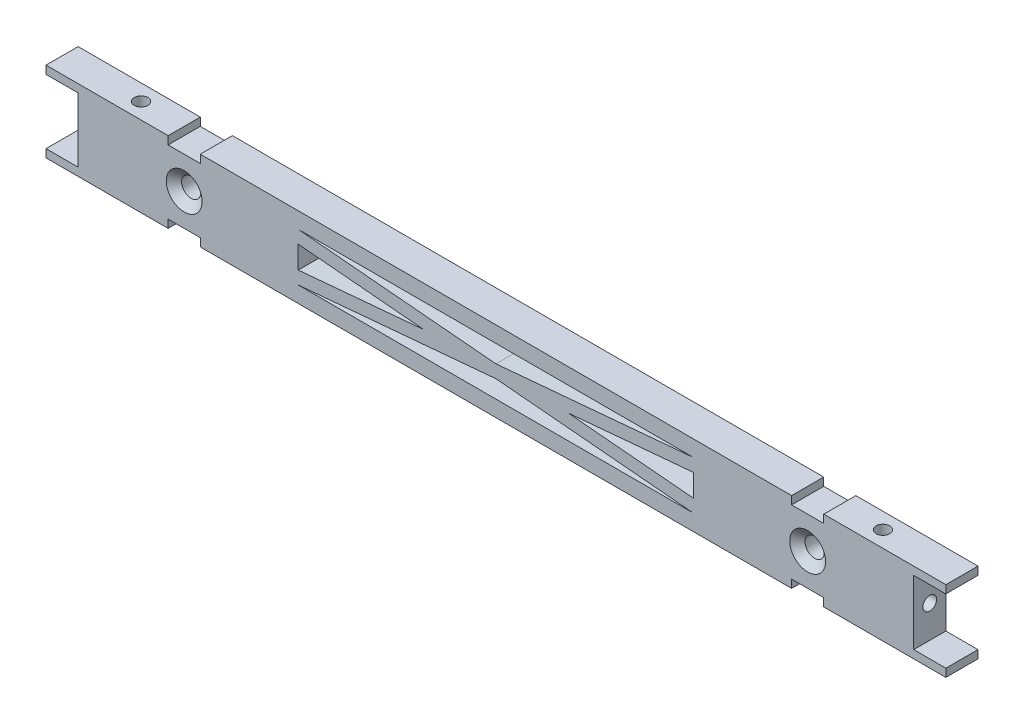
SolidWorks part; units mm, degrees
material "6061-T6 (SS)"
ref_plane "Front Plane" through (0, 0, 0) normal (0, 0, 1) x (1, 0, 0)
ref_plane "Top Plane" through (0, 0, 0) normal (0, 1, 0) x (1, 0, 0)
ref_plane "Right Plane" through (0, 0, 0) normal (1, 0, 0) x (0, 0, -1)
sketch "Sketch1" plane through (0, 0, 0) normal (0, 0, 1) x (1, 0, 0)
  line L0 (0, 7.9375) -> (0, -7.9375) construction
  line L1 (-88.9, 7.9375) -> (88.9, 7.9375)
  line L2 (-88.9, 7.9375) -> (-88.9, 6.35)
  line L3 (-88.9, -7.9375) -> (88.9, -7.9375)
  line L4 (88.9, 7.9375) -> (88.9, 6.35)
  line L5 (-88.9, 7.9375) -> (88.9, -7.9375) construction
  line L6 (-88.9, -7.9375) -> (88.9, 7.9375) construction
  line L7 (-88.9, 6.35) -> (-82.55, 6.35)
  line L8 (88.9, -6.35) -> (82.55, -6.35)
  line L9 (-88.9, -6.35) -> (-82.55, -6.35)
  line L10 (-82.55, 6.35) -> (-82.55, -6.35)
  line L11 (-88.9, -6.35) -> (-88.9, -7.9375)
  line L12 (82.55, 6.35) -> (82.55, -6.35)
  line L13 (88.9, 6.35) -> (82.55, 6.35)
  line L14 (88.9, -6.35) -> (88.9, -7.9375)
  line L15 (-89.0129, 6.6725) -> (88.7871, -9.2025)
  line L16 (-88.7871, -9.2025) -> (89.0129, 6.6725)
  line L17 (-88.7871, 9.2025) -> (89.0129, -6.6725)
  line L18 (-89.0129, -6.6725) -> (88.7871, 9.2025)
  line L20 (-39.0594, 4.7625) -> (39.0594, 4.7625)
  line L21 (-39.0594, 4.7625) -> (-39.0594, -4.7625)
  line L22 (-39.0594, -4.7625) -> (39.0594, -4.7625)
  line L23 (39.0594, 4.7625) -> (39.0594, -4.7625)
  point P0 (0, 0)
  dimension "D1" = 177.8
  dimension "D2" = 15.875
  dimension "D3" = 6.35
  dimension "D4" = 1.5875
  dimension "D5" = 1.5875
  dimension "D8" = 3.175
  dimension "D9" = 3.175
  dimension "D6" = 1.27
  dimension "D7" = 1.27
extrude "Boss-Extrude1" add sketch "Sketch1" along normal blind 6.35 contours L21 L15 L10 L18 | L22 L16 L3 L15 | L21 L18 L10 L9 L11 L3 L16 | L18 L21 L16 L15 | L17 L21 L15 L18 | L17 L20 L18 L1 | L21 L17 L1 L2 L15 L7 L10 | L23 L17 L16 L15 | L23 L18 L17 L16 | L18 L15 L16 L17 | L17 L23 L15 L3 L14 L8 L12 | L18 L23 L16 L12 L13 L4 L1 | L16 L13 L4 | L8 L17 L14 | L16 L23 L17 L12 | L11 L18 L9 | L15 L2 L7
ref_plane "Plane1" through (0, 0, 0) normal (1, 0, 0) x (0, 0, -1)
hole_wizard "Tap Drill for #6-32 Tap1" positions "Sketch3" profile "Sketch4" hole size "#6-32" standard "ANSI Inch"
sketch "Sketch3" plane through (-82.55, 0, 0) normal (-1, 0, 0) x (0, 0, 1)
  line L0 (6.35, 6.35) -> (0, 6.35) construction
  line L1 (0, 6.35) -> (0, -6.35) construction
  point P0 (3.175, 0)
  point P2 (3.175, 0)
  dimension "D1" = 6.35
  dimension "D2" = 6.35
  dimension "D3" = 3.175
  dimension "D4" = 3.175
sketch "Sketch4" plane through (-82.55, 0, 3.175) normal (0, 1, 0) x (0, 0, 1)
  line L0 (0, 0) -> (0, 13.5127)
  line L1 (0, 13.5127) -> (1.3525, 12.7)
  line L2 (1.3525, 12.7) -> (1.3525, 0)
  line L5 (1.3525, 0) -> (0, 0)
  line L10 (0, 13.5127) -> (-1.3526, 12.7) construction
  line L11 (0, -6.35) -> (0, 107.95) construction
  dimension "Hole Dia." = 2.7051
  dimension "Hole Depth" = 12.7
  dimension "Drill Angle" = 118
mirror "Mirror1" about plane through (0, 0, 0) normal (1, 0, 0) of "Tap Drill for #6-32 Tap1"
hole_wizard "Tap Drill for #6-32 Tap2" positions "Sketch6" profile "Sketch5" hole size "#6-32" standard "ANSI Inch"
sketch "Sketch6" plane through (0, 7.9375, 0) normal (0, 1, 0) x (1, 0, 0)
  line L0 (-88.9, -6.35) -> (-88.9, 0) construction
  point P0 (-73.2896, -3.175)
  point P9 (-88.9, -3.175)
  dimension "D1" = 15.6104
sketch "Sketch5" plane through (-73.2896, 7.9375, 3.175) normal (1, 0, 0) x (0, 0, 1)
  line L0 (0, 0) -> (0, 7.1627)
  line L1 (0, 7.1627) -> (1.3525, 6.35)
  line L2 (1.3525, 6.35) -> (1.3525, 0)
  line L5 (1.3525, 0) -> (0, 0)
  line L10 (0, 7.1627) -> (-1.3526, 6.35) construction
  line L11 (0, -6.35) -> (0, 107.95) construction
  dimension "Hole Dia." = 2.7051
  dimension "Hole Depth" = 6.35
  dimension "Drill Angle" = 118
ref_plane "Plane2" through (0, 0, 0) normal (0, -1, 0) x (-1, 0, 0)
mirror "Mirror2" about plane through (0, 0, 0) normal (1, 0, 0) of "Tap Drill for #6-32 Tap2"
mirror "Mirror3" about plane through (0, 0, 0) normal (0, -1, 0) of "Mirror2", "Tap Drill for #6-32 Tap2"
sketch "Sketch7" plane through (0, 0, 6.35) normal (0, 0, 1) x (1, 0, 0)
  line L0 (-64.77, 6.35) -> (-58.42, 6.35) construction
  line L1 (-64.77, 6.35) -> (-64.77, 7.9375) construction
  line L2 (-58.42, 6.35) -> (-58.42, 7.9375) construction
  line L3 (-64.77, 7.9375) -> (-58.42, 7.9375) construction
  line L4 (-64.77, -6.35) -> (-58.42, -6.35) construction
  line L5 (-64.77, -7.9375) -> (-64.77, -6.35) construction
  line L6 (-88.9, -7.9375) -> (88.9, -7.9375) construction
  line L7 (-58.42, -7.9375) -> (-58.42, -6.35) construction
  line L8 (58.42, -6.35) -> (58.42, -7.9375) construction
  line L9 (64.77, -6.35) -> (58.42, -6.35) construction
  line L10 (64.77, -6.35) -> (64.77, -7.9375) construction
  line L11 (58.42, 7.9375) -> (58.42, 6.35) construction
  line L12 (64.77, 6.35) -> (58.42, 6.35) construction
  line L13 (64.77, 7.9375) -> (64.77, 6.35) construction
  line L14 (64.77, 7.9375) -> (58.42, 7.9375) construction
  line L15 (-64.77, 6.35) -> (-58.42, 6.35)
  line L16 (-64.77, 6.35) -> (-64.77, 7.9375)
  line L17 (-58.42, 6.35) -> (-58.42, 7.9375)
  line L18 (-64.77, 7.9375) -> (-58.42, 7.9375)
  line L19 (-64.77, -6.35) -> (-58.42, -6.35)
  line L20 (-64.77, -7.9375) -> (-64.77, -6.35)
  line L21 (-64.77, -7.9375) -> (-58.42, -7.9375)
  line L22 (-58.42, -7.9375) -> (-58.42, -6.35)
  line L23 (58.42, -6.35) -> (58.42, -7.9375)
  line L24 (64.77, -6.35) -> (58.42, -6.35)
  line L25 (64.77, -6.35) -> (64.77, -7.9375)
  line L26 (58.42, 7.9375) -> (58.42, 6.35)
  line L27 (64.77, 6.35) -> (58.42, 6.35)
  line L28 (64.77, 7.9375) -> (64.77, 6.35)
  line L29 (64.77, 7.9375) -> (58.42, 7.9375)
  line L30 (58.42, -7.9375) -> (64.77, -7.9375)
extrude "Cut-Extrude1" cut sketch "Sketch7" against normal through all
hole_wizard "CSK for #6 Flat Head Machine Screw (100)1" positions "Sketch9" profile "Sketch8" countersink size "#6" standard "ANSI Inch" end condition through all
sketch "Sketch9" plane through (0, 0, 6.35) normal (0, 0, 1) x (1, 0, 0)
  line L0 (-64.77, 6.35) -> (-58.42, 6.35) construction
  line L1 (0, 7.9375) -> (0, -7.9375) construction
  line L2 (-58.42, 7.9375) -> (58.42, 7.9375) construction
  line L3 (-58.42, -7.9375) -> (58.42, -7.9375) construction
  point P0 (-61.595, 0)
  point P2 (-61.595, 0)
  point P7 (-61.595, 6.35)
  point P18 (61.595, 0)
  point P19 (61.595, 0)
  dimension "D1" = 7.9375
  dimension "D2" = 7.9375
sketch "Sketch8" plane through (-61.595, 0, 6.35) normal (1, 0, 0) x (0, -1, 0)
  line L0 (0, 0) -> (0, 6.35)
  line L1 (0, 6.35) -> (1.8986, 6.35)
  line L2 (1.8986, 6.35) -> (1.8986, 1.38)
  line L3 (1.8986, 1.38) -> (3.5433, 0)
  line L5 (3.5433, 0) -> (0, 0)
  line L6 (-1.8986, 1.38) -> (-3.5433, 0) construction
  line L11 (0, -6.35) -> (0, 107.95) construction
  dimension "Thru Hole Dia." = 3.7973
  dimension "Thru Hole Depth" = 6.35
  dimension "Near C'Sink Dia." = 7.0866
  dimension "Near C'Sink Angle" = 100
equation "\"D9@Sketch1\"=\"D8@Sketch1\""
